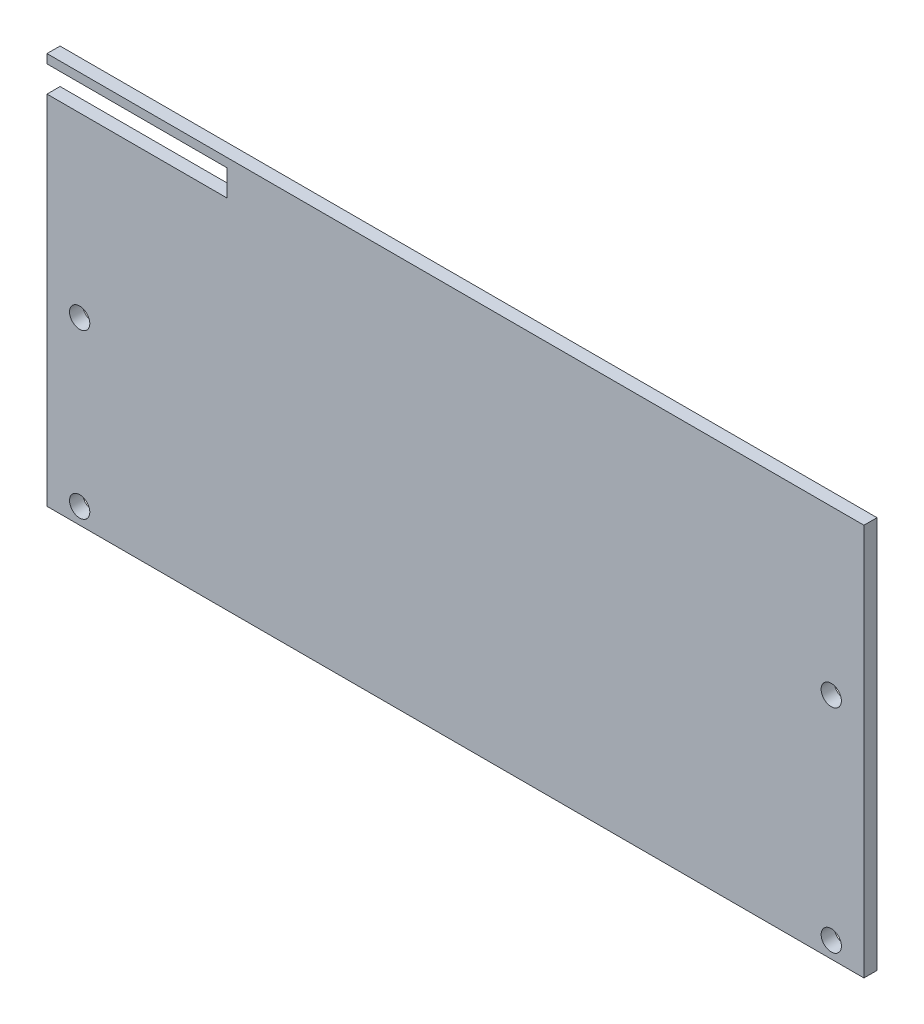
SolidWorks part; units mm, degrees
material "Teck"
ref_plane "Front Plane" through (0, 0, 0) normal (0, 0, 1) x (1, 0, 0)
ref_plane "Top Plane" through (0, 0, 0) normal (0, 1, 0) x (1, 0, 0)
ref_plane "Right Plane" through (0, 0, 0) normal (1, 0, 0) x (0, 0, -1)
sketch "Esquisse1" plane through (0, 0, 0) normal (0, 0, 1) x (1, 0, 0)
  line L1 (0, 0) -> (250, 0)
  line L2 (0, 0) -> (0, -120)
  line L3 (0, -120) -> (250, -120)
  line L4 (250, 0) -> (250, -120)
  line L5 (0, 0) -> (250, -120) construction
  line L6 (0, -120) -> (250, 0) construction
  circle A0 centre (10, -115) radius 3.1
  circle A1 centre (10, -65) radius 3.1
  circle A2 centre (240, -115) radius 3.1
  circle A3 centre (240, -50) radius 3.1
  point P4 (125, -60)
  dimension "D3" = 6.2
  dimension "D1" = 120
  dimension "D2" = 250
  dimension "D4" = 10
  dimension "D5" = 5
  dimension "D6" = 10
  dimension "D7" = 5
  dimension "D8" = 10
  dimension "D9" = 10
  dimension "D10" = 50
  dimension "D11" = 65
extrude "Boss.-Extru.1" add sketch "Esquisse1" along normal blind 4
sketch "Esquisse3" plane through (0, 0, 4) normal (0, 0, 1) x (1, 0, 0)
  line L0 (0, 0) -> (0, -120) construction
  line L1 (0, -2.7408) -> (55.1515, -2.7408)
  line L2 (0, -2.7408) -> (0, -10.7408)
  line L3 (0, -10.7408) -> (55.1515, -10.7408)
  line L4 (55.1515, -2.7408) -> (55.1515, -10.7408)
  line L5 (0, -2.7408) -> (55.1515, -10.7408) construction
  line L6 (0, -10.7408) -> (55.1515, -2.7408) construction
  line L7 (19.6703, -4.7408) -> (-6.6941, -4.7408) construction
  line L8 (41.5742, -8.7408) -> (-1.0979, -8.7408) construction
  point P4 (27.5757, -6.7408)
  dimension "D1" = 2
  dimension "D2" = 2
extrude "Enlèv. mat.-Extru.2" cut sketch "Esquisse3" against normal through all
